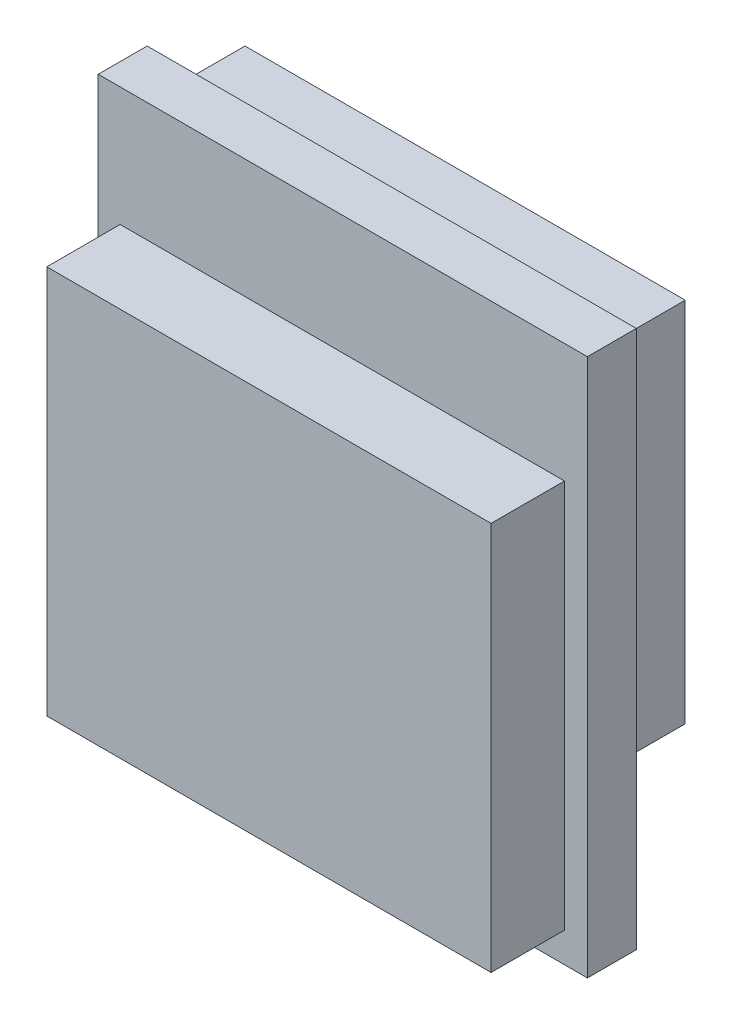
SolidWorks part; units mm, degrees
ref_plane "Front Plane" through (0, 0, 0) normal (0, 0, 1) x (1, 0, 0)
ref_plane "Top Plane" through (0, 0, 0) normal (0, 1, 0) x (1, 0, 0)
ref_plane "Right Plane" through (0, 0, 0) normal (1, 0, 0) x (0, 0, -1)
sketch "Sketch1" plane through (0, 0, 0) normal (0, 0, 1) x (1, 0, 0)
  line L0 (-68.5859, -300) -> (-68.5859, 60) construction
  line L4 (-77.5859, -132.4785) -> (-59.5859, -132.4785)
  line L5 (-77.5859, -132.4785) -> (-77.5859, -147.4785)
  line L6 (-77.5859, -147.4785) -> (-59.5859, -147.4785)
  line L7 (-59.5859, -132.4785) -> (-59.5859, -147.4785)
extrude "Boss-Extrude1" add sketch "Sketch1" along normal blind 3 contours L6 L7 L4 L5
sketch "Sketch2" plane through (0, 0, 3) normal (0, 0, 1) x (1, 0, 0)
  line L0 (-77.5859, -132.4785) -> (-77.5859, -147.4785) construction
  line L1 (-78.5859, -131.4785) -> (-58.5859, -131.4785)
  line L2 (-78.5859, -131.4785) -> (-78.5859, -153.4785)
  line L3 (-78.5859, -153.4785) -> (-58.5859, -153.4785)
  line L4 (-58.5859, -131.4785) -> (-58.5859, -153.4785)
  line L5 (-77.5859, -132.4785) -> (-59.5859, -132.4785) construction
  dimension "D1" = 22
  dimension "D2" = 20
  dimension "D3" = 1
  dimension "D4" = 1
extrude "Boss-Extrude2" add sketch "Sketch2" along normal blind 2
sketch "Sketch3" plane through (0, 0, 5) normal (0, 0, 1) x (1, 0, 0)
  line L1 (-77.6905, -152.253) -> (-59.5236, -152.253)
  line L2 (-77.6905, -152.253) -> (-77.6905, -136.3495)
  line L3 (-77.6905, -136.3495) -> (-59.5236, -136.3495)
  line L4 (-59.5236, -152.253) -> (-59.5236, -136.3495)
extrude "Boss-Extrude3" add sketch "Sketch3" along normal blind 3
